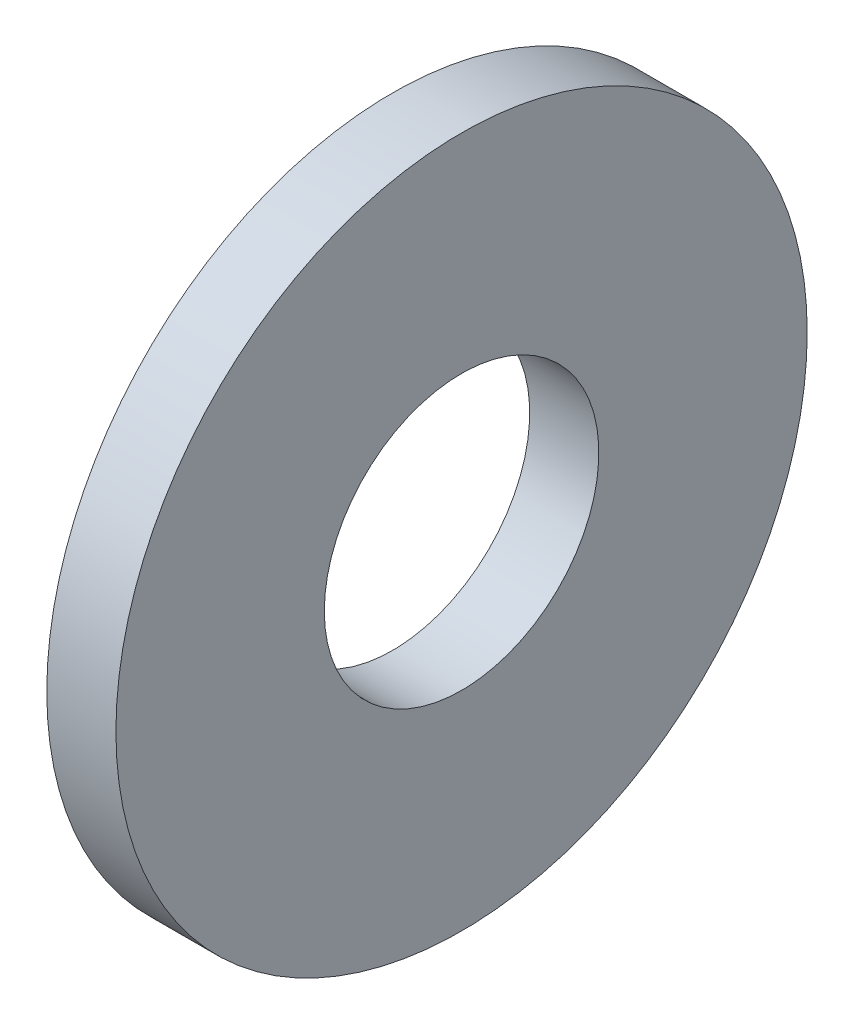
SolidWorks part; units mm, degrees
ref_plane "Plane1" through (0, 0, 0) normal (0, 0, 1) x (1, 0, 0)
ref_plane "Plane2" through (0, 0, 0) normal (0, 1, 0) x (1, 0, 0)
ref_plane "Plane3" through (0, 0, 0) normal (1, 0, 0) x (0, 0, -1)
sketch "Sketch1" plane through (0, 0, 0) normal (0, 0, 1) x (1, 0, 0)
  line L0 (-34.925, 0) -> (9.525, 0) construction
  line L1 (0, 5.56) -> (0, 14)
  line L2 (0, 14) -> (-2.8, 14)
  line L3 (-2.8, 14) -> (-2.8, 5.56)
  line L4 (-2.8, 5.56) -> (0, 5.56)
  dimension "Thickness" = 2.8
  dimension "Inside_dia" = 11.12
  dimension "Outside_dia" = 28
revolve "Base-Revolve" add sketch "Sketch1" angle 360 about L0
